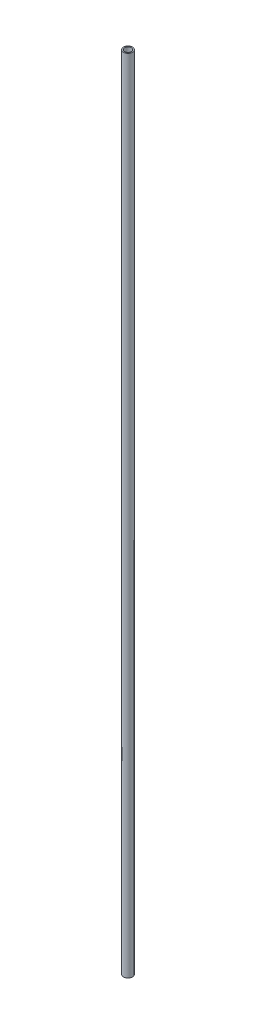
SolidWorks part; units mm, degrees
material "Hexcel AS4C (3000 Filaments)"
ref_plane "Front Plane" through (0, 0, 0) normal (0, 0, 1) x (1, 0, 0)
ref_plane "Top Plane" through (0, 0, 0) normal (0, 1, 0) x (1, 0, 0)
ref_plane "Right Plane" through (0, 0, 0) normal (1, 0, 0) x (0, 0, -1)
sketch "Sketch1" plane through (0, 0, 0) normal (0, 1, 0) x (1, 0, 0)
  circle A0 centre (0, 0) radius 4
  circle A1 centre (0, 0) radius 3
  dimension "D1" = 8
  dimension "D2" = 6
extrude "Boss-Extrude1" add sketch "Sketch1" against normal mid plane 710
ref_plane "Plane1" through (0, 0, 0) normal (1, 0, 0) x (0, 0, -1)
